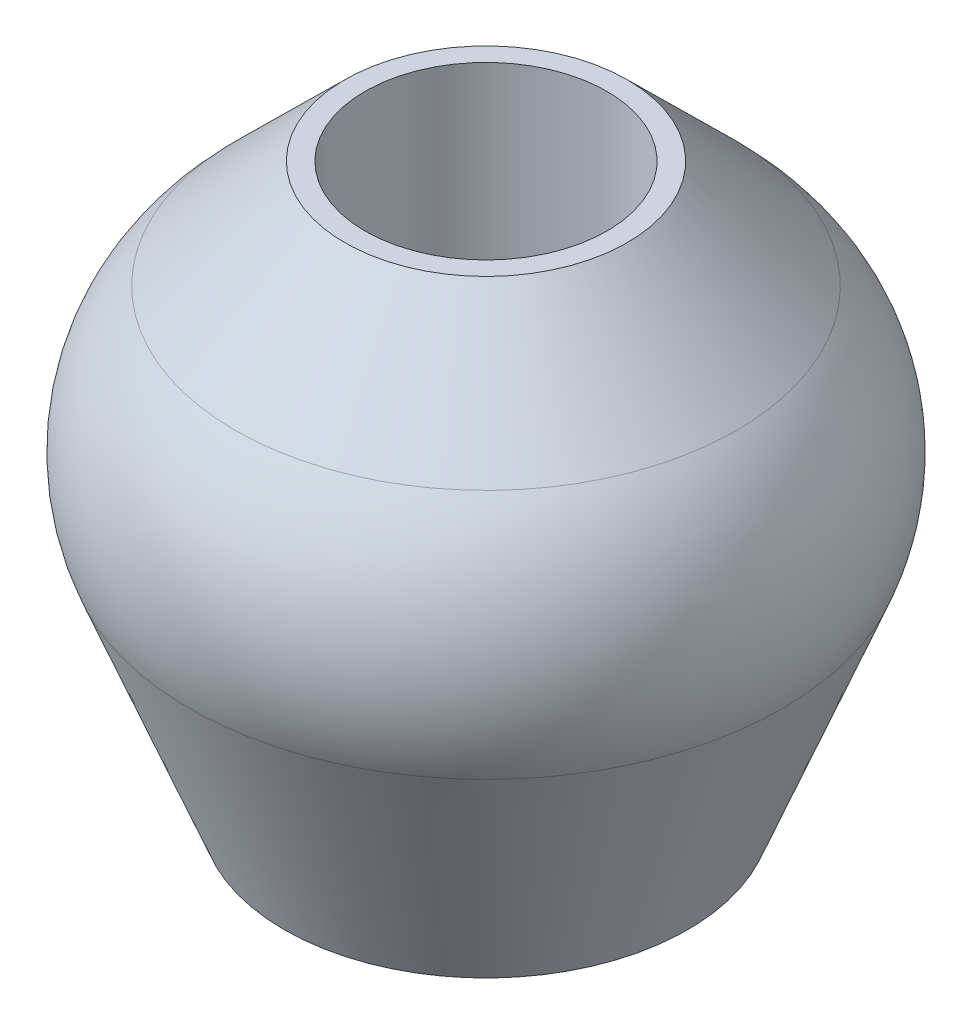
SolidWorks part; units mm, degrees
ref_plane "Front Plane" through (0, 0, 0) normal (0, 0, 1) x (1, 0, 0)
ref_plane "Top Plane" through (0, 0, 0) normal (0, 1, 0) x (1, 0, 0)
ref_plane "Right Plane" through (0, 0, 0) normal (1, 0, 0) x (0, 0, -1)
sketch "Sketch1" plane through (0, 0, 0) normal (1, 0, 0) x (0, 0, -1)
  line L0 (0, 0) -> (0, 14) construction
  line L1 (0, 0) -> (5, 0)
  line L2 (5, 0) -> (8.5669, 9)
  line L3 (8.5669, 9) -> (3.5, 14)
  line L4 (3.5, 14) -> (0, 14)
  line L5 (0, 14) -> (0, 0)
  dimension "D1" = 5
  dimension "D2" = 9
  dimension "D3" = 5
  dimension "D4" = 113
  dimension "D5" = 3.5
revolve "Revolve1" add sketch "Sketch1" angle 360 about L0
hole_wizard "M8 Tapped Hole1" positions "Sketch2" profile "Sketch3" tap size "M8" standard "ISO"
sketch "Sketch2" plane through (0, 14, 0) normal (0, 1, 0) x (1, 0, 0)
  point P0 (0, 0)
sketch "Sketch3" plane through (0, 14, 0) normal (1, 0, 0) x (0, 0, 1)
  line L0 (0, 0) -> (0, 9.75)
  line L1 (0, 9.75) -> (3, 9.75)
  line L2 (3, 9.75) -> (3, 0)
  line L5 (3, 0) -> (0, 0)
  line L10 (0, 9.75) -> (-3, 9.75) construction
  line L11 (0, -6.35) -> (0, 107.95) construction
  dimension "Tap Drill Dia." = 6
  dimension "Tap Drill Depth" = 9.75
  dimension "Drill Angle" = 180
cosmetic thread "Hole Thread1"
fillet "Fillet1" radius 5 1 edges at (0, 9, -8.5669)
